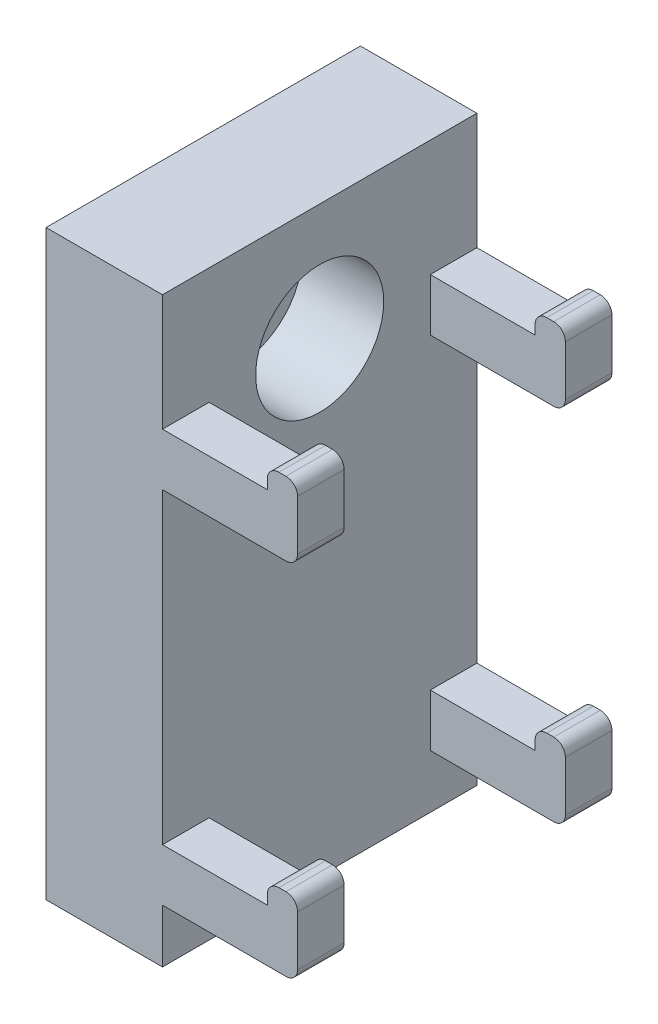
SolidWorks part; units mm, degrees
ref_plane "Front Plane" through (0, 0, 0) normal (0, 0, 1) x (1, 0, 0)
ref_plane "Top Plane" through (0, 0, 0) normal (0, 1, 0) x (1, 0, 0)
ref_plane "Right Plane" through (0, 0, 0) normal (1, 0, 0) x (0, 0, -1)
sketch "Sketch1" plane through (0, 0, 0) normal (1, 0, 0) x (0, 0, -1)
  line L0 (-22.1162, 10) -> (20.8126, 10) construction
  line L7 (-13.5, 10) -> (13.5, 10)
  line L8 (-13.5, 10) -> (-13.5, -40)
  line L9 (-13.5, -40) -> (13.5, -40)
  line L10 (13.5, 10) -> (13.5, -40)
  point P8 (-0.6518, 10)
  dimension "D1" = 10
  dimension "D2" = 27
  dimension "D3" = 13.5
  dimension "D4" = 50
extrude "Boss-Extrude1" add sketch "Sketch1" along normal blind 10
sketch "Sketch2" plane through (10, 0, 0) normal (1, 0, 0) x (0, 0, -1)
  line L3 (0, 55) -> (0, -55) construction
  circle A0 centre (0, 0) radius 3.5
  dimension "D2" = 7
extrude "Cut-Extrude1" cut sketch "Sketch2" against normal blind 10
sketch "Sketch3" plane through (10, 0, 0) normal (1, 0, 0) x (0, 0, -1)
  circle A0 centre (0, 0) radius 5.5
  dimension "D1" = 11
extrude "Cut-Extrude2" cut sketch "Sketch3" against normal blind 7
sketch "Sketch4" plane through (0, 0, 13.5) normal (0, 0, 1) x (1, 0, 0)
  line L0 (10, 0) -> (19, 0)
  line L2 (10, -4.5) -> (20.6, -4.5)
  line L3 (21.6, -3.5) -> (21.6, 0.8)
  line L4 (20.6, 1.8) -> (20, 1.8)
  line L5 (19, 0.8) -> (19, 0)
  line L6 (10, -30.9) -> (19, -30.9)
  line L7 (19, -30.9) -> (19, -30.1)
  line L8 (20, -29.1) -> (20.6, -29.1)
  line L9 (21.6, -30.1) -> (21.6, -34.4)
  line L10 (20.6, -35.4) -> (10, -35.4)
  line L11 (10, 0) -> (10, -4.5)
  line L12 (10, -30.9) -> (10, -35.4)
  line L13 (10, 10) -> (10, -40) construction
  line L14 (10, -3.5) -> (10, 3.5) construction
  arc A0 (21.6, -34.4) -> (20.6, -35.4) centre (20.6, -34.4) cw
  arc A1 (20.6, -4.5) -> (21.6, -3.5) centre (20.6, -3.5) ccw
  arc A2 (20.6, -29.1) -> (21.6, -30.1) centre (20.6, -30.1) cw
  arc A3 (19, -30.1) -> (20, -29.1) centre (20, -30.1) cw
  arc A4 (21.6, 0.8) -> (20.6, 1.8) centre (20.6, 0.8) ccw
  arc A5 (20, 1.8) -> (19, 0.8) centre (20, 0.8) ccw
  point P23 (19, -29.1)
  point P28 (19, 1.8)
  dimension "D10" = 1
  dimension "D1" = 4.5
  dimension "D2" = 11.6
  dimension "D3" = 4.5
  dimension "D4" = 2.6
  dimension "D5" = 9
  dimension "D6" = 9
  dimension "D7" = 30.9
  dimension "D8" = 1.8
  dimension "D9" = 1.8
  dimension "D11" = 11.6
extrude "Boss-Extrude2" add sketch "Sketch4" against normal blind 4
mirror "Mirror1" about plane through (0, 0, 0) normal (0, 0, 1) of "Boss-Extrude2"
ref_plane "Plane1" through (0, 0, 6) normal (0, 0, 1) x (1, 0, 0)
ref_plane "Plane2" through (0, 0, -6) normal (0, 0, 1) x (1, 0, 0)
sketch "Sketch8" plane through (0, 0, -6) normal (0, 0, 1) x (1, 0, 0)
  line L0 (5, 5) -> (5, 12.8202) construction
  line L6 (5, 11.9966) -> (5, 10)
  line L7 (10, 10) -> (0, 10) construction
  line L8 (5, 10) -> (7.1161, 10)
  arc A1 (7.1161, 10) -> (5, 11.9966) centre (5.1161, 10) ccw
  dimension "D1" = 2
  dimension "D2" = 1.9966
revolve "Revolve1" [suppressed] add sketch "Sketch8" angle 360 about L0
mirror "Mirror2" [suppressed] about plane through (0, 0, 0) normal (0, 0, 1)
sketch "Sketch9" plane through (0, 10, 0) normal (0, 1, 0) x (1, 0, 0)
  line L0 (5.9672, 0.0466) -> (5.9672, 0.726)
  line L1 (5.9672, 0.726) -> (7.6021, 0.2453)
  line L2 (7.6021, 0.2453) -> (7.6021, -0.2445)
  line L3 (7.6021, -0.2445) -> (5.9672, -0.7252)
  line L4 (5.9672, -0.7252) -> (5.9672, 0.0466)
  line L5 (5.4672, 1.3942) -> (5.4672, -1.3934)
  line L6 (5.4672, -1.3934) -> (7.6436, -0.7534)
  line L7 (5.4672, 1.3942) -> (7.6436, 0.7542)
  line L8 (7.4642, 1.0757) -> (7.7663, 1.338)
  line L9 (7.5555, -0.9494) -> (7.8981, -1.1559)
  arc A0 (7.9907, 0.0004) -> (7.7663, 1.338) centre (6.7847, 0.4857) ccw
  arc A1 (7.9907, 0.0004) -> (7.8981, -1.1559) centre (6.7847, -0.4848) cw
  arc A2 (7.4642, 1.0757) -> (7.6436, 0.7542) centre (6.7847, 0.4857) cw
  arc A3 (7.6436, -0.7534) -> (7.5446, -0.9669) centre (6.7847, -0.4848) cw
  dimension "D4" = 1.3
  dimension "D5" = 1.3
  dimension "D6" = 0.9
  dimension "D7" = 0.9
  dimension "D1" = 0.5
  dimension "D2" = 0.5
  dimension "D3" = 0.5
extrude "Cut-Extrude4" [suppressed] cut sketch "Sketch9" against normal blind 1 contours L6 A3 L9 A1 A0 L8 A2 L7 L5 L3 L4 L0 L1 L2
ref_plane "Plane18" through (10, 0, 13.5) normal (1, 0, 0) x (0, 0, -1)
